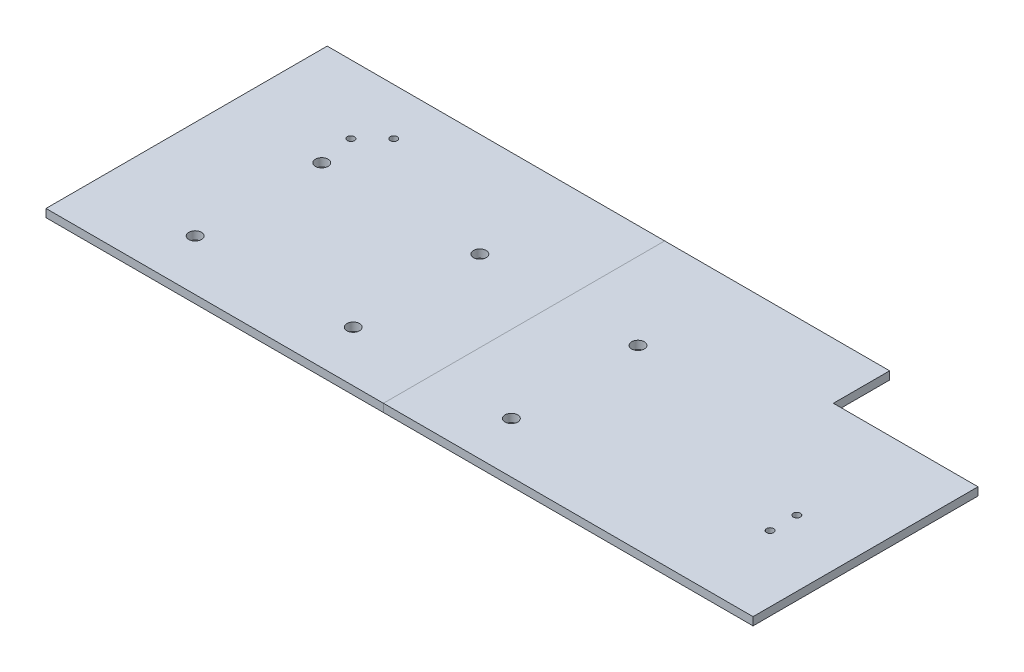
SolidWorks part; units mm, degrees
other "Markup1"
sketch "Sketch4" plane through (-552.45, -6.35, -222.25) normal (-0.3259, -0.6642, -0.6728) x (-0.9221, 0.3804, 0.0712)
sketch "Sketch11" plane through (-552.45, -39.4589, -222.25) normal (-0.3259, -0.6642, -0.6728) x (-0.9221, 0.3804, 0.0712)
sketch "Sketch13" plane through (-552.45, -39.4589, -222.25) normal (-0.3259, -0.6642, -0.6728) x (-0.9221, 0.3804, 0.0712)
sketch "Sketch15" plane through (-552.45, -39.4589, -222.25) normal (-0.3259, -0.6642, -0.6728) x (-0.9221, 0.3804, 0.0712)
sketch "Sketch17" plane through (-552.45, -39.4589, -222.25) normal (-0.3259, -0.6642, -0.6728) x (-0.9221, 0.3804, 0.0712)
sketch "Sketch19" plane through (-558.8, 0, -222.25) normal (-0.3259, -0.6642, -0.6728) x (-0.9221, 0.3804, 0.0712)
sketch "Sketch24" plane through (-558.8, 0, -222.25) normal (-0.3259, -0.6642, -0.6728) x (-0.9221, 0.3804, 0.0712)
other "Markup2"
sketch "Sketch5" plane through (-552.45, -6.35, -222.25) normal (-0.3259, -0.6642, -0.6728) x (-0.9221, 0.3804, 0.0712)
sketch "Sketch12" plane through (-552.45, -39.4589, -222.25) normal (-0.3259, -0.6642, -0.6728) x (-0.9221, 0.3804, 0.0712)
sketch "Sketch14" plane through (-552.45, -39.4589, -222.25) normal (-0.3259, -0.6642, -0.6728) x (-0.9221, 0.3804, 0.0712)
sketch "Sketch16" plane through (-552.45, -39.4589, -222.25) normal (-0.3259, -0.6642, -0.6728) x (-0.9221, 0.3804, 0.0712)
sketch "Sketch18" plane through (-552.45, -39.4589, -222.25) normal (-0.3259, -0.6642, -0.6728) x (-0.9221, 0.3804, 0.0712)
sketch "Sketch20" plane through (-558.8, 0, -222.25) normal (-0.3259, -0.6642, -0.6728) x (-0.9221, 0.3804, 0.0712)
sketch "Sketch25" plane through (-558.8, 0, -222.25) normal (-0.3259, -0.6642, -0.6728) x (-0.9221, 0.3804, 0.0712)
ref_plane "Front Plane" through (0, 0, 0) normal (0, 0, 1) x (1, 0, 0)
ref_plane "Top Plane" through (0, 0, 0) normal (0, 1, 0) x (1, 0, 0)
ref_plane "Right Plane" through (0, 0, 0) normal (1, 0, 0) x (0, 0, -1)
sketch "Sketch1" plane through (0, 0, 0) normal (0, 1, 0) x (1, 0, 0)
  line L0 (0, 0) -> (0, 177.8)
  line L1 (0, 177.8) -> (-114.3, 177.8)
  line L2 (-114.3, 177.8) -> (-114.3, 222.25)
  line L3 (-114.3, 222.25) -> (-558.8, 222.25)
  line L4 (-558.8, 222.25) -> (-558.8, 0)
  line L5 (-558.8, 0) -> (0, 0)
  dimension "D1" = 177.8
  dimension "D2" = 114.3
  dimension "D3" = 558.8
  dimension "D4" = 222.25
extrude "Boss-Extrude1" add sketch "Sketch1" along normal blind 6.35
sketch "Sketch2" plane through (0, 0, 0) normal (0, -1, 0) x (1, 0, 0)
  line L1 (0, 0) -> (0, -177.8) construction
  line L6 (0, -107.95) -> (-33.1089, -107.95) construction
  line L7 (-33.1089, -107.95) -> (-33.1089, -44.45) construction
  line L10 (0, -177.8) -> (-114.3, -177.8) construction
  line L11 (-6.35, -44.45) -> (-33.1089, -44.45) construction
  line L12 (-33.1089, -44.45) -> (-39.4589, -44.45) construction
  line L13 (-39.4589, -44.45) -> (-39.4589, -107.95) construction
  line L14 (-39.4589, -107.95) -> (-33.1089, -107.95) construction
  line L15 (-39.4589, -107.95) -> (-64.8589, -107.95) construction
  line L17 (-64.8589, -107.95) -> (-64.8589, -44.45) construction
  line L18 (-64.8589, -44.45) -> (-39.4589, -44.45) construction
  line L19 (-52.1589, -44.45) -> (-52.1589, -107.95) construction
  line L20 (-64.8589, -86.7833) -> (-39.4589, -86.7833) construction
  line L21 (-64.8589, -65.6167) -> (-39.4589, -65.6167) construction
  line L22 (-33.1089, -44.45) -> (-509.3589, -44.45) construction
  line L23 (-509.3589, -44.45) -> (-509.3589, -151.3205) construction
  line L24 (-509.3589, -151.3205) -> (-509.3589, -100.5205) construction
  line L25 (-509.3589, -100.5205) -> (-503.0089, -100.5205) construction
  line L26 (-503.0089, -100.5205) -> (-503.0089, -202.1205) construction
  line L27 (-503.0089, -202.1205) -> (-509.3589, -202.1205) construction
  line L28 (-509.3589, -202.1205) -> (-509.3589, -151.3205) construction
  line L29 (-503.0089, -151.3205) -> (-452.2089, -151.3205) construction
  line L30 (-503.0089, -202.1205) -> (-452.2089, -202.1205) construction
  line L31 (-452.2089, -202.1205) -> (-452.2089, -151.3205) construction
  line L32 (-452.2089, -202.1205) -> (-503.0089, -151.3205) construction
  line L33 (-452.2089, -202.1205) -> (-469.1422, -185.1872) construction
  line L34 (-469.1422, -185.1872) -> (-486.0756, -168.2538) construction
  line L35 (-486.0756, -168.2538) -> (-503.0089, -151.3205) construction
  circle A0 centre (-52.1589, -86.7833) radius 2.7781
  circle A1 centre (-52.1589, -65.6167) radius 2.7781
  circle A2 centre (-469.1422, -185.1872) radius 2.7781
  circle A3 centre (-486.0756, -168.2538) radius 2.7781
  dimension "D9" = 5.5562
  dimension "D16" = 5.5562
  dimension "D1" = 33.1089
  dimension "D2" = 6.35
  dimension "D3" = 25.4
  dimension "D4" = 69.85
  dimension "D5" = 26.7589
  dimension "D6" = 63.5
  dimension "D7" = 21.1667
  dimension "D8" = 21.1667
  dimension "D10" = 476.25
  dimension "D11" = 106.8705
  dimension "D12" = 50.8
  dimension "D13" = 50.8
  dimension "D14" = 6.35
  dimension "D15" = 50.8
sketch "Sketch10" plane through (0, 6.35, 0) normal (0, 1, 0) x (1, 0, 0)
  line L0 (-481.076, 40.132) -> (-481.076, 0) construction
  line L1 (-481.076, 222.25) -> (-481.076, 180.34) construction
  line L2 (-558.8, 40.132) -> (-546.1, 40.132) construction
  line L3 (-114.3, 222.25) -> (-558.8, 222.25) construction
  line L4 (-481.076, 180.34) -> (-481.076, 140.208) construction
  line L5 (-558.8, 222.25) -> (-558.8, 0) construction
  line L6 (-546.1, 40.132) -> (-481.076, 40.132) construction
  line L7 (-558.8, 0) -> (0, 0) construction
  circle A0 centre (-481.076, 40.132) radius 5
  circle A1 centre (-356.108, 40.132) radius 5
  circle A2 centre (-231.14, 40.132) radius 5
  circle A3 centre (-356.108, 140.208) radius 5
  circle A4 centre (-231.14, 140.208) radius 5
  circle A5 centre (-481.076, 140.208) radius 5
  dimension "D3" = 10
  dimension "D4" = 12.7
  dimension "D6" = 124.968
  dimension "D7" = 100.076
  dimension "D8" = 40.132
  dimension "D9" = 65.024
  dimension "D1" = 3
  dimension "D2" = 2
extrude "Cut-Extrude3" cut sketch "Sketch10" against normal through all both and the other way through all
extrude "Cut-Extrude4" cut sketch "Sketch2" against normal through all
sketch "Sketch23" plane through (0, 6.35, 0) normal (0, 1, 0) x (1, 0, 0)
  line L0 (-356.108, 140.208) -> (-231.14, 140.208) construction
  line L1 (-368.808, 152.908) -> (-368.808, 127.508) construction
  line L2 (-356.108, 140.208) -> (-368.808, 140.208) construction
  line L3 (-368.808, 152.908) -> (-218.44, 152.908)
  line L4 (-218.44, 152.908) -> (-218.44, 127.508)
  line L5 (-218.44, 127.508) -> (-368.808, 127.508)
  line L6 (-231.14, 140.208) -> (-218.44, 140.208) construction
  circle A0 centre (-356.108, 140.208) radius 5 construction
  circle A2 centre (-231.14, 140.208) radius 5 construction
  point P9 (-356.108, 140.208)
  point P10 (-368.808, 140.208)
  dimension "D1" = 10
  dimension "D2" = 25.4
  dimension "D3" = 12.7
sketch "Sketch28" plane through (0, 6.35, 0) normal (0, 1, 0) x (1, 0, 0)
  line L0 (-292.1, 222.25) -> (-292.1, 0)
  line L1 (-114.3, 222.25) -> (-558.8, 222.25) construction
  line L2 (-558.8, 0) -> (0, 0) construction
  line L3 (-558.8, 222.25) -> (-558.8, 0) construction
  dimension "D1" = 266.7
split "Split1" trim tools "Sketch28" bodies to split 114 resulting bodies 115 116
